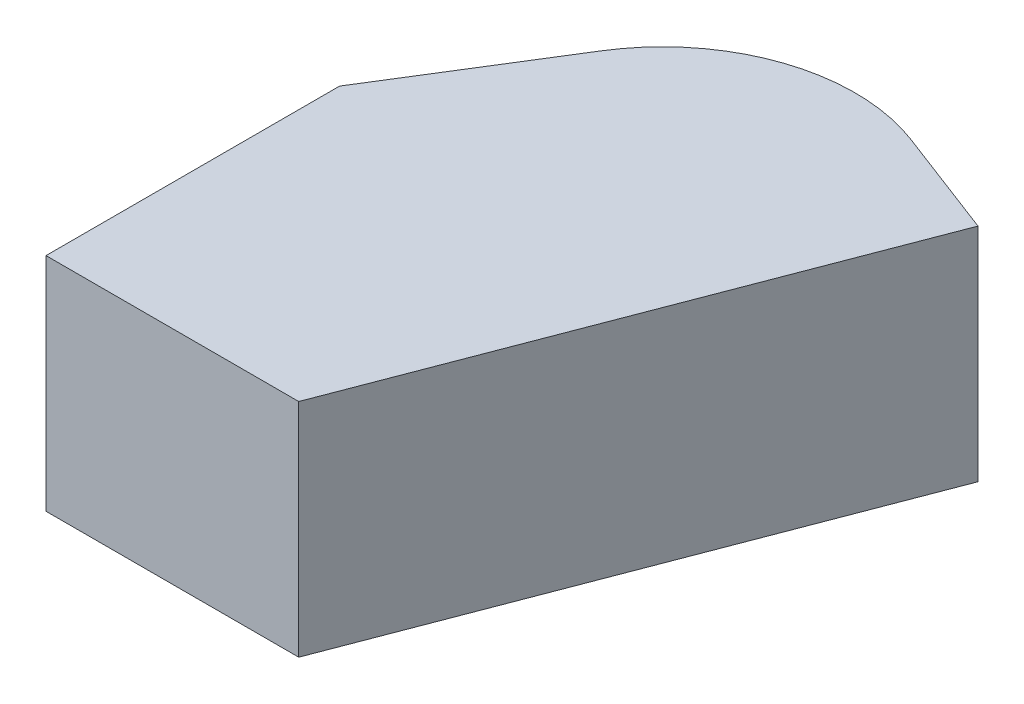
SolidWorks part; units mm, degrees
material "Pure Gold"
ref_plane "Front Plane" through (0, 0, 0) normal (0, 0, 1) x (1, 0, 0)
ref_plane "Top Plane" through (0, 0, 0) normal (0, 1, 0) x (1, 0, 0)
ref_plane "Right Plane" through (0, 0, 0) normal (1, 0, 0) x (0, 0, -1)
sketch "Sketch1" plane through (0, 0, 0) normal (0, 1, 0) x (1, 0, 0)
  line L0 (-66.6738, 0) -> (-40.2757, 42.4721)
  line L1 (0, 0) -> (-66.6738, 0) construction
  line L2 (0, 0) -> (0, -77.4519) construction
  line L3 (0, -77.4519) -> (-66.6738, -77.4519)
  line L4 (-66.6738, 0) -> (-66.6738, -77.4519)
  line L5 (20.9897, 63.114) -> (49.5116, 52.2241)
  line L6 (49.5116, 52.2241) -> (0, -77.4519)
  arc A0 (-40.2757, 42.4721) -> (20.9897, 63.114) centre (2.8696, 15.6556) cw
  point P5 (49.5116, 52.2241)
  dimension "D1" = 50.8
extrude "Boss-Extrude1" add sketch "Sketch1" along normal blind 58.42
